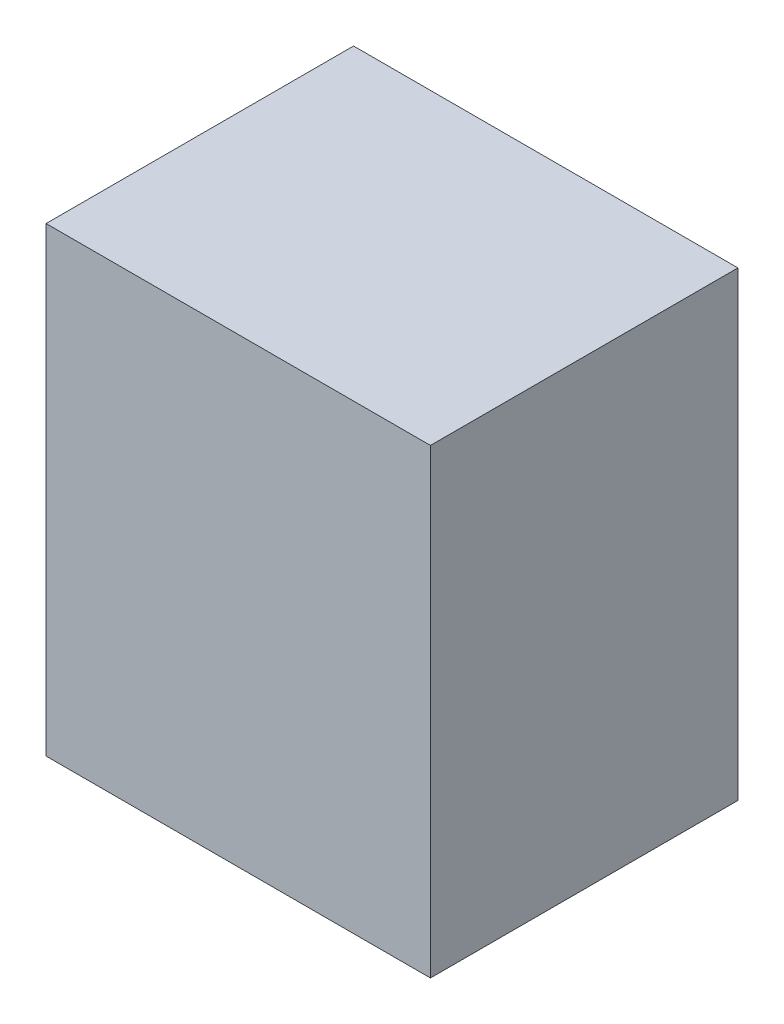
SolidWorks part; units mm, degrees
ref_plane "Front Plane" through (0, 0, 0) normal (0, 0, 1) x (1, 0, 0)
ref_plane "Top Plane" through (0, 0, 0) normal (0, 1, 0) x (1, 0, 0)
ref_plane "Right Plane" through (0, 0, 0) normal (1, 0, 0) x (0, 0, -1)
sketch "Sketch1" plane through (0, 0, 0) normal (0, 0, 1) x (1, 0, 0)
  line L1 (0, 0) -> (100, 0)
  line L2 (0, 0) -> (0, 120)
  line L3 (0, 120) -> (100, 120)
  line L4 (100, 0) -> (100, 120)
  dimension "D1" = 120
  dimension "D2" = 100
extrude "Boss-Extrude1" add sketch "Sketch1" along normal blind 80
sketch "Sketch3" plane through (0, 120, 0) normal (0, 1, 0) x (1, 0, 0)
  line L0 (100, 0) -> (0, 0) construction
  line L2 (0, -80) -> (0, 0) construction
  circle A0 centre (50, -40) radius 5.5
  circle A1 centre (50, -40) radius 10.845
  dimension "D1" = 40
  dimension "D2" = 50
  dimension "D3" = 11
  dimension "D4" = 21.69
